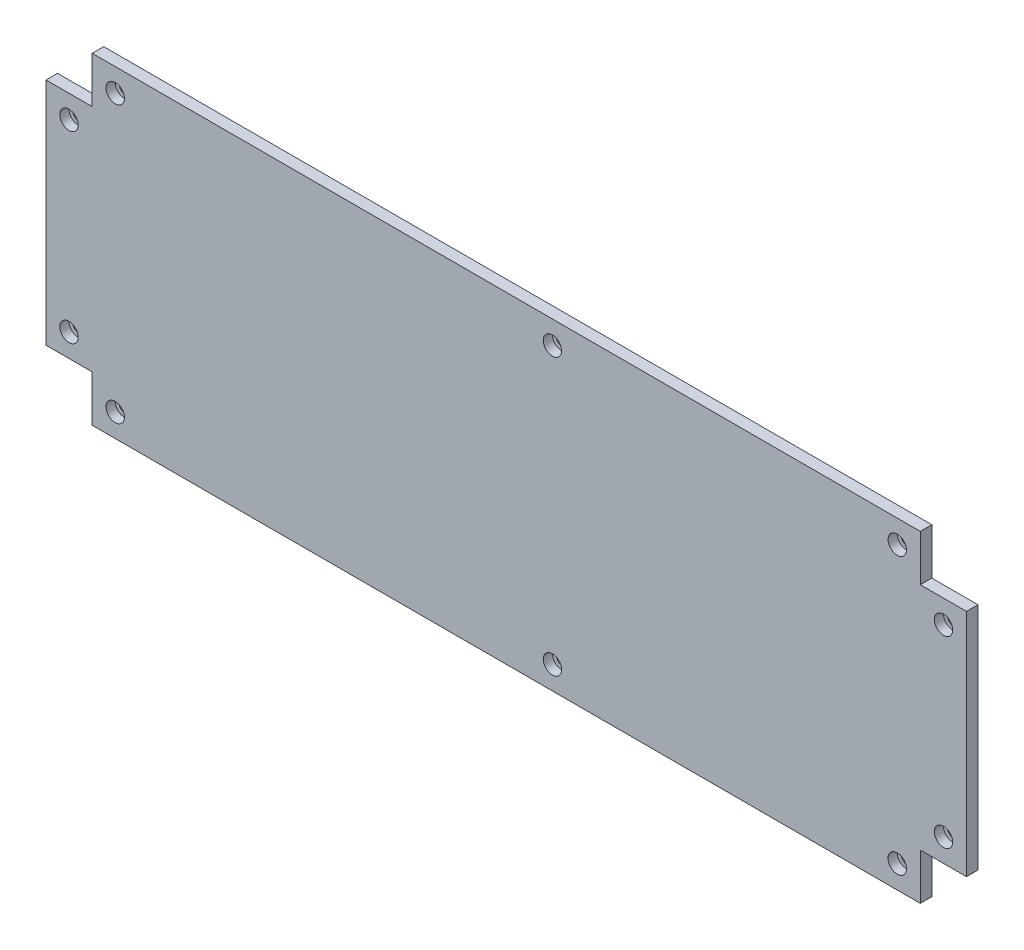
SolidWorks part; units mm, degrees
ref_plane "정면" through (0, 0, 0) normal (0, 0, 1) x (1, 0, 0)
ref_plane "윗면" through (0, 0, 0) normal (0, 1, 0) x (1, 0, 0)
ref_plane "우측면" through (0, 0, 0) normal (1, 0, 0) x (0, 0, -1)
sketch "스케치1" plane through (0, 0, 0) normal (0, 0, 1) x (1, 0, 0)
  line L0 (-20.08, 0) -> (0, 0)
  line L1 (0, 0) -> (0, 20.08)
  line L2 (0, 20.08) -> (359.84, 20.08)
  line L3 (359.84, 20.08) -> (359.84, 0)
  line L4 (359.84, 0) -> (379.92, 0)
  line L5 (379.92, 0) -> (379.92, -99.84)
  line L6 (379.92, -99.84) -> (359.84, -99.84)
  line L7 (359.84, -99.84) -> (359.84, -119.92)
  line L8 (359.84, -119.92) -> (0, -119.92)
  line L9 (0, -119.92) -> (0, -99.84)
  line L10 (0, -99.84) -> (-20.08, -99.84)
  line L11 (-20.08, -99.84) -> (-20.08, 0)
  point P11 (0, 0)
  dimension "D1" = 20.08
  dimension "D2" = 20.08
  dimension "D3" = 359.84
  dimension "D4" = 20.08
  dimension "D5" = 99.84
  dimension "D6" = 20.08
  dimension "D7" = 20.08
  dimension "D8" = 359.84
  dimension "D9" = 20.08
  dimension "D10" = 20.08
extrude "보스-돌출1" add sketch "스케치1" along normal blind 5
hole_wizard "M4 소켓 머리 캡 나사용 카운터보어1" positions "스케치3" profile "스케치4" counterbore size "M4" standard "KS" end condition through all
sketch "스케치3" plane through (0, 0, 5) normal (0, 0, 1) x (1, 0, 0)
  line L0 (-20.08, 0) -> (-20.08, -99.84) construction
  line L1 (0, 0) -> (-20.08, 0) construction
  line L2 (-20.08, -99.84) -> (0, -99.84) construction
  line L3 (0, -99.84) -> (0, -119.92) construction
  line L5 (0, -119.92) -> (359.84, -119.92) construction
  line L6 (359.84, -119.92) -> (359.84, -99.84) construction
  line L7 (359.84, -99.84) -> (379.92, -99.84) construction
  line L8 (379.92, -99.84) -> (379.92, 0) construction
  line L9 (379.92, 0) -> (359.84, 0) construction
  line L10 (359.84, 0) -> (359.84, 20.08) construction
  line L11 (359.84, 20.08) -> (0, 20.08) construction
  line L12 (0, 20.08) -> (0, 0) construction
  line L13 (0, 20.08) -> (0, 0) construction
  point P0 (-10.08, -10)
  point P2 (-10.08, -89.84)
  point P4 (10, -109.92)
  point P6 (200, -109.92)
  point P8 (349.84, -109.92)
  point P10 (369.92, -89.84)
  point P12 (369.92, -10)
  point P14 (349.84, 10.08)
  point P16 (200, 10.08)
  point P18 (10, 10.08)
  point P33 (11.0839, -119.92)
  dimension "D1" = 10
  dimension "D2" = 10
  dimension "D3" = 10
  dimension "D4" = 10
  dimension "D5" = 10
  dimension "D6" = 10
  dimension "D7" = 200
  dimension "D8" = 10
  dimension "D9" = 10
  dimension "D10" = 10
  dimension "D11" = 10
  dimension "D12" = 10
  dimension "D13" = 10
  dimension "D14" = 10
  dimension "D15" = 10
  dimension "D16" = 10
  dimension "D17" = 200
  dimension "D18" = 10
  dimension "D19" = 10
  dimension "D20" = 10
sketch "스케치4" plane through (-10.08, -10, 5) normal (1, 0, 0) x (0, -1, 0)
  line L0 (0, 0) -> (0, 5)
  line L1 (0, 5) -> (2.25, 5)
  line L3 (2.25, 5) -> (2.25, 4)
  line L4 (2.25, 4) -> (4, 4)
  line L5 (4, 4) -> (4, 0)
  line L7 (4, 0) -> (0, 0)
  line L11 (0, -6.35) -> (0, 107.95) construction
  dimension "관통 구멍 지름" = 4.5
  dimension "관통 구멍 깊이" = 5
  dimension "카운터보어 지름" = 8
  dimension "카운터보어 깊이" = 4
